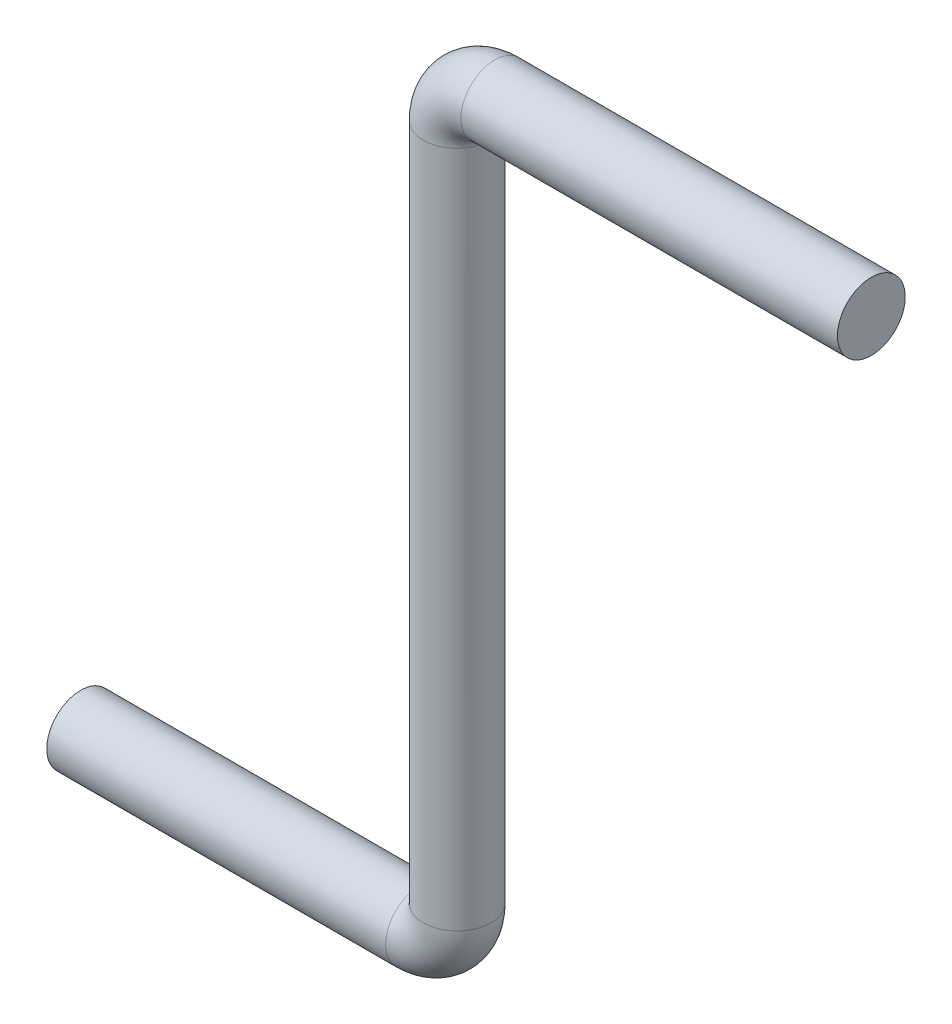
SolidWorks part; units mm, degrees
ref_plane "Front Plane" through (0, 0, 0) normal (0, 0, 1) x (1, 0, 0)
ref_plane "Top Plane" through (0, 0, 0) normal (0, 1, 0) x (1, 0, 0)
ref_plane "Right Plane" through (0, 0, 0) normal (1, 0, 0) x (0, 0, -1)
sketch "Sketch1" plane through (0, 0, 0) normal (0, 0, 1) x (1, 0, 0)
  line L0 (0, 4.5) -> (0, -4.5)
  line L1 (-0.5, -5) -> (-5, -5)
  line L2 (0.5, 5) -> (5.5, 5)
  arc A0 (0, -4.5) -> (-0.5, -5) centre (-0.5, -4.5) cw
  arc A1 (0, 4.5) -> (0.5, 5) centre (0.5, 4.5) cw
  point P4 (0, 0)
  point P8 (0, -5)
  point P9 (0, -5)
  point P12 (0, 5)
  point P20 (5.5, 5)
  dimension "D3" = 0.5
  dimension "D1" = 10
  dimension "D2" = 5
  dimension "D6" = 5
sweep "Sweep1" add path "Sketch1" circular profile diameter 0.9 parameters "D3"=0.9
